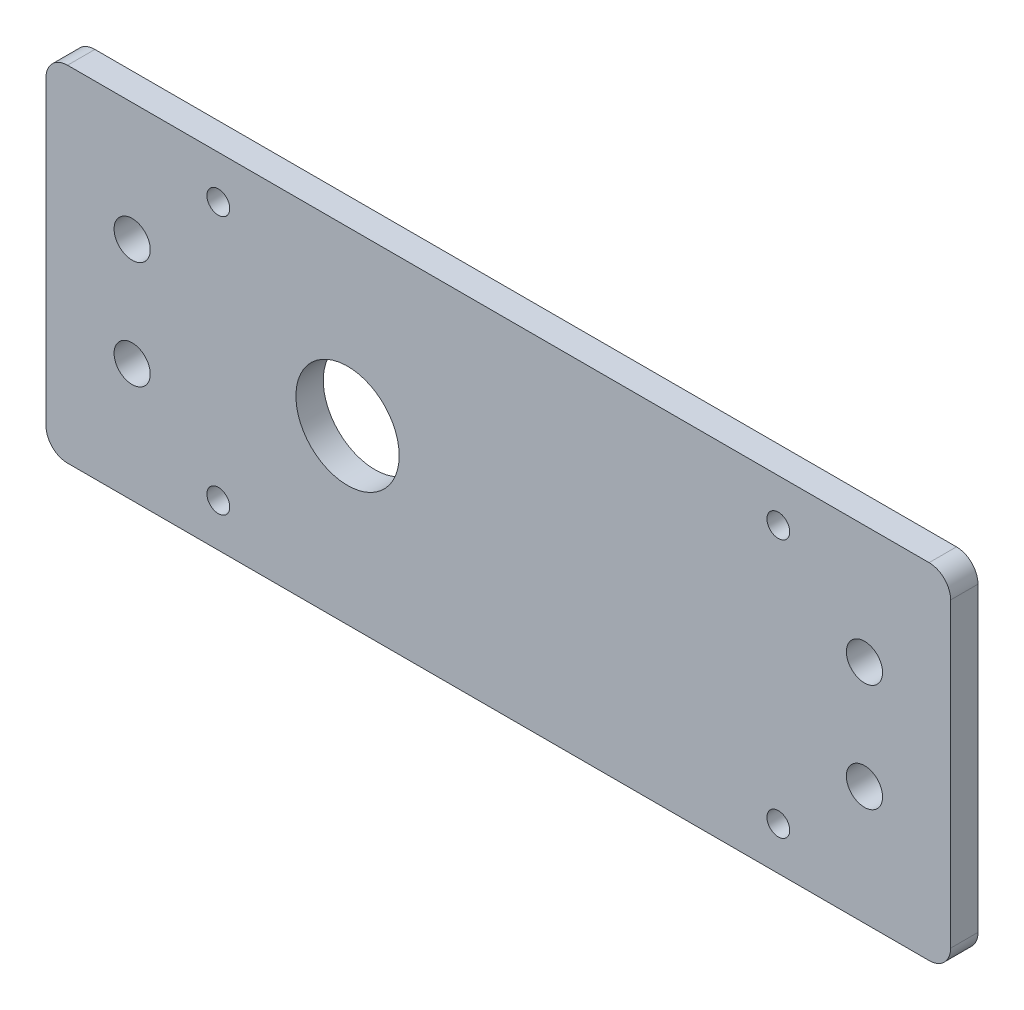
SolidWorks part; units mm, degrees
material "5052-H32"
ref_plane "Front Plane" through (0, 0, 0) normal (0, 0, 1) x (1, 0, 0)
ref_plane "Top Plane" through (0, 0, 0) normal (0, 1, 0) x (1, 0, 0)
ref_plane "Right Plane" through (0, 0, 0) normal (1, 0, 0) x (0, 0, -1)
sketch "Sketch1" plane through (0, 0, 0) normal (0, 0, 1) x (1, 0, 0)
  line L0 (-30, 30) -> (100, 30) construction
  line L1 (-70, 40) -> (140, 40)
  line L2 (-70, 40) -> (-70, -40)
  line L3 (-70, -40) -> (140, -40)
  line L4 (140, 40) -> (140, -40)
  line L5 (-30, 30) -> (-30, -30) construction
  line L6 (35.3553, -35.3553) -> (0, 0) construction
  line L7 (-50, 12.5) -> (120, 12.5) construction
  line L8 (-50, 12.5) -> (-50, -12.5) construction
  line L9 (-50, -12.5) -> (120, -12.5) construction
  line L10 (120, 12.5) -> (120, -12.5) construction
  line L11 (0, 0) -> (50, 0) construction
  circle A0 centre (0, 0) radius 11.9875
  circle A1 centre (-30, 30) radius 2.5 construction
  circle A2 centre (100, 30) radius 2.5 construction
  circle A3 centre (-30, -30) radius 2.5 construction
  circle A4 centre (100, -30) radius 2.5 construction
  circle A5 centre (-50, 12.5) radius 4 construction
  circle A6 centre (-50, -12.5) radius 4 construction
  circle A7 centre (120, -12.5) radius 4 construction
  circle A8 centre (120, 12.5) radius 4 construction
  circle A9 centre (50, 0) radius 40 construction
  arc A10 (50, 0) -> (35.3553, -35.3553) centre (0, 0) cw construction
  circle A11 centre (35.3553, -35.3553) radius 40 construction
  point P20 (-50, 0)
  point P28 (-30, 0)
  point P29 (-98.2068, -38.079)
  point P30 (-94.2737, 39.9859)
  point P31 (-70, 0)
  point P32 (35, 40)
  point P34 (35, 12.5)
  dimension "D1" = 23.975
  dimension "D6" = 60
  dimension "D7" = 5
  dimension "D2" = 8
  dimension "D9" = 20
  dimension "D11" = 80
  dimension "D12" = 50
  dimension "D3" = 20
  dimension "D4" = 130
  dimension "D5" = 10
  dimension "D8" = 30
  dimension "D10" = 25
  dimension "D13" = 45
  dimension "D14" = 20
extrude "Boss-Extrude1" add sketch "Sketch1" against normal blind 6.35 contours L1 L4 L3 L2
hole_wizard "M5 Clearance Hole1" positions "3DSketch1" profile "Sketch2" hole size "M5" standard "ANSI Metric" end condition up to next
sketch3d "3DSketch1"
  point P0 (-30, 30, 0)
  point P2 (-30, -30, 0)
  point P4 (100, -30, 0)
  point P6 (100, 30, 0)
  point P10 (-50, 12.5, 0)
  point P12 (-50, -12.5, 0)
  point P14 (50, 12.5, 0)
  point P16 (50, -12.5, 0)
sketch "Sketch2" plane through (-30, 30, 0) normal (1, 0, 0) x (0, -1, 0)
  line L0 (0, 0) -> (0, 6.35)
  line L1 (0, 6.35) -> (2.65, 6.35)
  line L2 (2.65, 6.35) -> (2.65, 0)
  line L5 (2.65, 0) -> (0, 0)
  line L11 (0, -6.35) -> (0, 107.95) construction
  dimension "Thru Hole Dia." = 5.3
  dimension "Thru Hole Depth" = 6.35
fillet "Fillet1" radius 5 4 edges at (140, -40, -3.175) (140, 40, -3.175) (-70, -40, -3.175) (-70, 40, -3.175)
hole_wizard "M8 Clearance Hole2" positions "3DSketch2" profile "Sketch3" hole size "M8" standard "ANSI Metric" end condition up to next
sketch3d "3DSketch2"
  point P0 (-50, 12.5, 0)
  point P2 (-50, -12.5, 0)
  point P4 (120, -12.5, 0)
  point P6 (120, 12.5, 0)
  point P9 (-70, 12.5, 0)
  point P11 (-70, -12.5, 0)
  point P13 (130, -12.5, 0)
  point P15 (130, 12.5, 0)
sketch "Sketch3" plane through (-50, 12.5, 0) normal (1, 0, 0) x (0, -1, 0)
  line L0 (0, 0) -> (0, 6.35)
  line L1 (0, 6.35) -> (4.2, 6.35)
  line L2 (4.2, 6.35) -> (4.2, 0)
  line L5 (4.2, 0) -> (0, 0)
  line L11 (0, -6.35) -> (0, 107.95) construction
  dimension "Thru Hole Dia." = 8.4
  dimension "Thru Hole Depth" = 6.35
